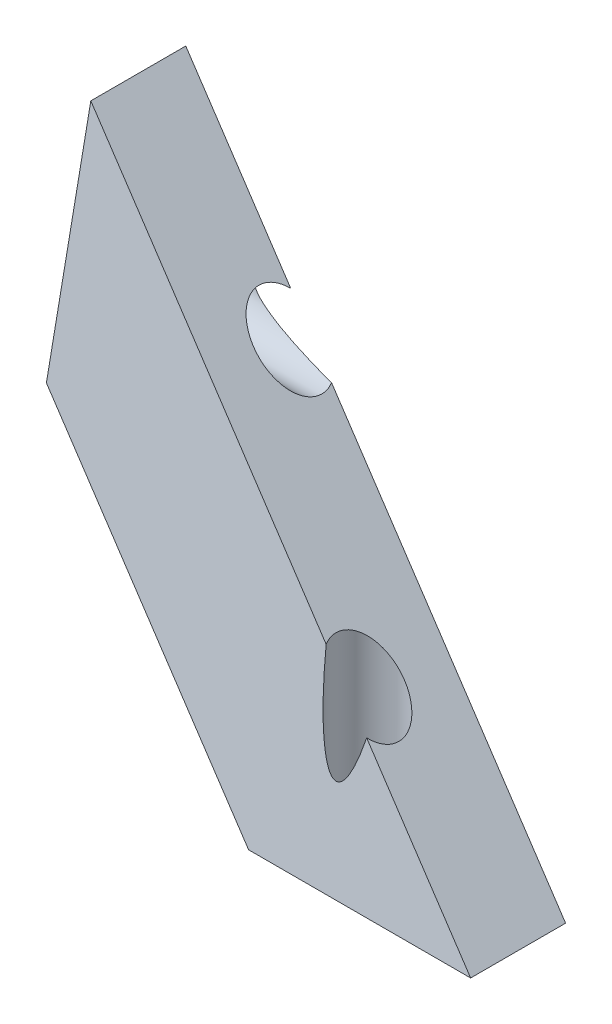
SolidWorks part; units mm, degrees
ref_plane "Front Plane" through (0, 0, 0) normal (0, 0, 1) x (1, 0, 0)
ref_plane "Top Plane" through (0, 0, 0) normal (0, 1, 0) x (1, 0, 0)
ref_plane "Right Plane" through (0, 0, 0) normal (1, 0, 0) x (0, 0, -1)
sketch "Sketch2" plane through (0, 0, 0) normal (0, 1, 0) x (1, 0, 0)
  line L1 (-57.5079, -22.2465) -> (5.9921, -22.2465)
  line L2 (-57.5079, -22.2465) -> (-57.5079, 3.1535)
  line L3 (-57.5079, 3.1535) -> (5.9921, 3.1535)
  line L4 (5.9921, -22.2465) -> (5.9921, 3.1535)
extrude "Boss-Extrude1" add sketch "Sketch2" along normal blind 63.5
sketch "Sketch3" plane through (0, 0, 22.2465) normal (0, 0, 1) x (1, 0, 0)
  line L0 (-57.5079, 63.5) -> (5.9921, 0)
  line L1 (5.9921, 0) -> (5.9921, 63.5)
  line L2 (5.9921, 63.5) -> (-57.5079, 63.5)
extrude "Cut-Extrude1" cut sketch "Sketch3" against normal through all
sketch "Sketch4" plane through (0, 0, 0) normal (0, -1, 0) x (1, 0, 0)
  line L0 (-57.5079, 22.2465) -> (5.9921, 22.2465) construction
  line L1 (-54.5079, 17.8465) -> (-50.3079, 17.8465)
  line L2 (-54.5079, 17.8465) -> (-54.5079, 13.6465)
  line L3 (-54.5079, 13.6465) -> (-50.3079, 13.6465)
  line L4 (-50.3079, 17.8465) -> (-50.3079, 13.6465)
  line L5 (-57.5079, -3.1535) -> (-57.5079, 22.2465) construction
  line L6 (-41.8079, 17.8465) -> (-41.8079, 13.6465)
  line L7 (-41.8079, 17.8465) -> (-37.6079, 17.8465)
  line L8 (-37.6079, 17.8465) -> (-37.6079, 13.6465)
  line L9 (-41.8079, 13.6465) -> (-37.6079, 13.6465)
  line L10 (-29.1079, 17.8465) -> (-29.1079, 13.6465)
  line L11 (-29.1079, 17.8465) -> (-24.9079, 17.8465)
  line L12 (-24.9079, 17.8465) -> (-24.9079, 13.6465)
  line L13 (-29.1079, 13.6465) -> (-24.9079, 13.6465)
  line L14 (-16.4079, 17.8465) -> (-16.4079, 13.6465)
  line L15 (-16.4079, 17.8465) -> (-12.2079, 17.8465)
  line L16 (-12.2079, 17.8465) -> (-12.2079, 13.6465)
  line L17 (-16.4079, 13.6465) -> (-12.2079, 13.6465)
  line L18 (-3.7079, 17.8465) -> (-3.7079, 13.6465)
  line L19 (-3.7079, 17.8465) -> (0.4921, 17.8465)
  line L20 (0.4921, 17.8465) -> (0.4921, 13.6465)
  line L21 (-3.7079, 13.6465) -> (0.4921, 13.6465)
  point P4 (-52.4079, 17.8465)
  dimension "D1" = 4.4
  dimension "D2" = 3
  dimension "D3" = 4.2
  dimension "D4" = 4.2
  dimension "D5" = 5
extrude "Boss-Extrude2" add sketch "Sketch4" along normal blind 3.5
sketch "Sketch5" plane through (-57.5079, 0, 0) normal (-1, 0, 0) x (0, 0, 1)
  line L0 (-3.1535, 63.5) -> (-3.1535, 0) construction
  line L1 (1.2465, 3.4) -> (5.4465, 3.4)
  line L2 (1.2465, 3.4) -> (1.2465, 7.6)
  line L3 (1.2465, 7.6) -> (5.4465, 7.6)
  line L4 (5.4465, 3.4) -> (5.4465, 7.6)
  line L5 (-3.1535, 0) -> (22.2465, 0) construction
  line L6 (1.2465, 15.9) -> (1.2465, 20.1)
  line L7 (1.2465, 15.9) -> (5.4465, 15.9)
  line L8 (5.4465, 15.9) -> (5.4465, 20.1)
  line L9 (1.2465, 20.1) -> (5.4465, 20.1)
  line L10 (1.2465, 28.4) -> (1.2465, 32.6)
  line L11 (1.2465, 28.4) -> (5.4465, 28.4)
  line L12 (5.4465, 28.4) -> (5.4465, 32.6)
  line L13 (1.2465, 32.6) -> (5.4465, 32.6)
  line L14 (1.2465, 40.9) -> (1.2465, 45.1)
  line L15 (1.2465, 40.9) -> (5.4465, 40.9)
  line L16 (5.4465, 40.9) -> (5.4465, 45.1)
  line L17 (1.2465, 45.1) -> (5.4465, 45.1)
  line L18 (1.2465, 53.4) -> (1.2465, 57.6)
  line L19 (1.2465, 53.4) -> (5.4465, 53.4)
  line L20 (5.4465, 53.4) -> (5.4465, 57.6)
  line L21 (1.2465, 57.6) -> (5.4465, 57.6)
  dimension "D1" = 4.2
  dimension "D2" = 4.4
  dimension "D3" = 3.4
  dimension "D4" = 5
extrude "Boss-Extrude3" add sketch "Sketch5" along normal blind 3.5
sketch "Sketch6" plane through (-57.5079, 0, 0) normal (-1, 0, 0) x (0, 0, 1)
  line L0 (22.2465, 0) -> (9.5465, 63.5)
  line L1 (-3.1535, 63.5) -> (22.2465, 63.5) construction
  line L2 (9.5465, 63.5) -> (22.2465, 63.5)
  line L3 (22.2465, 63.5) -> (22.2465, 0)
sketch "Sketch7" plane through (0, 0, 0) normal (0, -1, 0) x (1, 0, 0)
  line L0 (-57.5079, -3.1535) -> (5.9921, 9.5465)
  line L1 (5.9921, 22.2465) -> (5.9921, -3.1535) construction
  line L2 (5.9921, 9.5465) -> (5.9921, -3.1535)
  line L3 (5.9921, -3.1535) -> (-57.5079, -3.1535)
fillet "Fillet1" radius 1.5 40 edges at (-59.2579, 7.6, 5.4465) (-59.2579, 7.6, 1.2465) (-59.2579, 3.4, 1.2465) (-59.2579, 3.4, 5.4465) (-59.2579, 20.1, 1.2465) (-59.2579, 15.9, 1.2465) (-59.2579, 15.9, 5.4465) (-59.2579, 20.1, 5.4465) (-59.2579, 28.4, 1.2465) (-59.2579, 32.6, 5.4465) (-59.2579, 32.6, 1.2465) (-59.2579, 28.4, 5.4465) (-59.2579, 45.1, 1.2465) (-59.2579, 40.9, 1.2465) (-59.2579, 40.9, 5.4465) (-59.2579, 45.1, 5.4465) (-59.2579, 53.4, 1.2465) (-59.2579, 57.6, 1.2465) (-59.2579, 57.6, 5.4465) (-59.2579, 53.4, 5.4465) (0.4921, -1.75, 17.8465) (0.4921, -1.75, 13.6465) (-3.7079, -1.75, 13.6465) (-3.7079, -1.75, 17.8465) (-12.2079, -1.75, 13.6465) (-16.4079, -1.75, 13.6465) (-16.4079, -1.75, 17.8465) (-12.2079, -1.75, 17.8465) (-29.1079, -1.75, 13.6465) (-24.9079, -1.75, 13.6465) (-29.1079, -1.75, 17.8465) (-24.9079, -1.75, 17.8465) (-41.8079, -1.75, 13.6465) (-37.6079, -1.75, 13.6465) (-37.6079, -1.75, 17.8465) (-41.8079, -1.75, 17.8465) (-50.3079, -1.75, 13.6465) (-50.3079, -1.75, 17.8465) (-54.5079, -1.75, 13.6465) (-54.5079, -1.75, 17.8465)
extrude "Cut-Extrude4" cut sketch "Sketch6" against normal through all
extrude "Cut-Extrude5" cut sketch "Sketch7" against normal through all
sketch "Sketch8" plane through (0, -3.5, 0) normal (0, -1, 0) x (1, 0, 0)
  circle A2 centre (-14.3079, 15.7465) radius 2.385
extrude "Cut-Extrude6" cut sketch "Sketch8" against normal through all
sketch3d "3DSketch1"
  line L1 (-12.5407, 23.2041, 15.1253) -> (-12.5407, 23.2041, 19.2722)
  line L2 (-14.3079, 0, 15.7465) -> (-14.3079, 32.1646, 15.7465)
  line L4 (-14.3079, 22.685, 15.7465) -> (-14.3079, 0, 15.7465) construction
  line L5 (-12.5407, 23.2041, 15.1253) -> (-15.9149, 23.2041, 15.1253)
ref_plane "Plane1" through (0, 23.2041, 0) normal (0, 1, 0) x (1, 0, 0)
sketch "Sketch12" plane through (0, 23.2041, 0) normal (0, 1, 0) x (1, 0, 0)
  circle A1 centre (-14.3079, -15.7465) radius 4.2
extrude "Cut-Extrude7" cut sketch "Sketch12" against normal blind 18 and the other way blind 10
sketch "Sketch13" plane through (-61.0079, 0, 0) normal (-1, 0, 0) x (0, 0, 1)
  circle A2 centre (3.3465, 43) radius 2.385
extrude "Cut-Extrude8" cut sketch "Sketch13" against normal through all
sketch3d "3DSketch2"
  line L1 (-57.5079, 43, 3.3465) -> (-27.0683, 43, 3.3465)
  line L2 (-33.5531, 43.1921, 3.2726) -> (-33.5531, 43.1921, 6.0147)
  line L3 (-36.9259, 43, 3.3465) -> (-57.5079, 43, 3.3465) construction
  line L5 (-33.5531, 43.1921, 6.0147) -> (-33.5531, 41.6802, 6.0147)
ref_plane "Plane2" through (-33.5531, 0, 0) normal (-1, 0, 0) x (0, 0, 1)
sketch "Sketch14" plane through (-33.5531, 0, 0) normal (-1, 0, 0) x (0, 0, 1)
  circle A1 centre (3.3465, 43) radius 4.2
extrude "Cut-Extrude9" cut sketch "Sketch14" against normal blind 10 and the other way blind 20
ref_plane "Plane3" through (-11.8532, -11.8532, 0) normal (0.7071, 0.7071, 0) x (0.7071, -0.7071, 0)
sketch "Sketch15" plane through (-11.8532, -11.8532, 0) normal (0.7071, 0.7071, 0) x (0.7071, -0.7071, 0)
  line L1 (-5.9575, 3.9012) -> (-77.8063, 3.9012)
  line L2 (-5.9575, 3.9012) -> (-5.9575, -22.8076)
  line L3 (-5.9575, -22.8076) -> (-77.8063, -22.8076)
  line L4 (-77.8063, 3.9012) -> (-77.8063, -22.8076)
extrude "Cut-Extrude10" cut sketch "Sketch15" against normal blind 30
